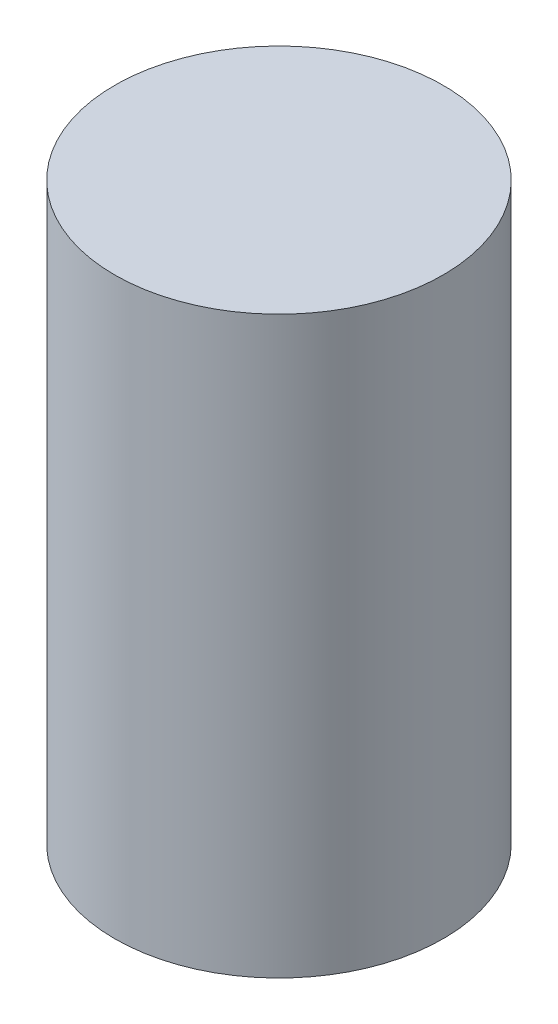
SolidWorks part; units mm, degrees
ref_plane "Front Plane" through (0, 0, 0) normal (0, 0, 1) x (1, 0, 0)
ref_plane "Top Plane" through (0, 0, 0) normal (0, 1, 0) x (1, 0, 0)
ref_plane "Right Plane" through (0, 0, 0) normal (1, 0, 0) x (0, 0, -1)
sketch "Sketch1" plane through (0, 0, 0) normal (0, 1, 0) x (1, 0, 0)
  circle A0 centre (0, 0) radius 20
  dimension "D1" = 40
extrude "Boss-Extrude1" add sketch "Sketch1" along normal blind 70
